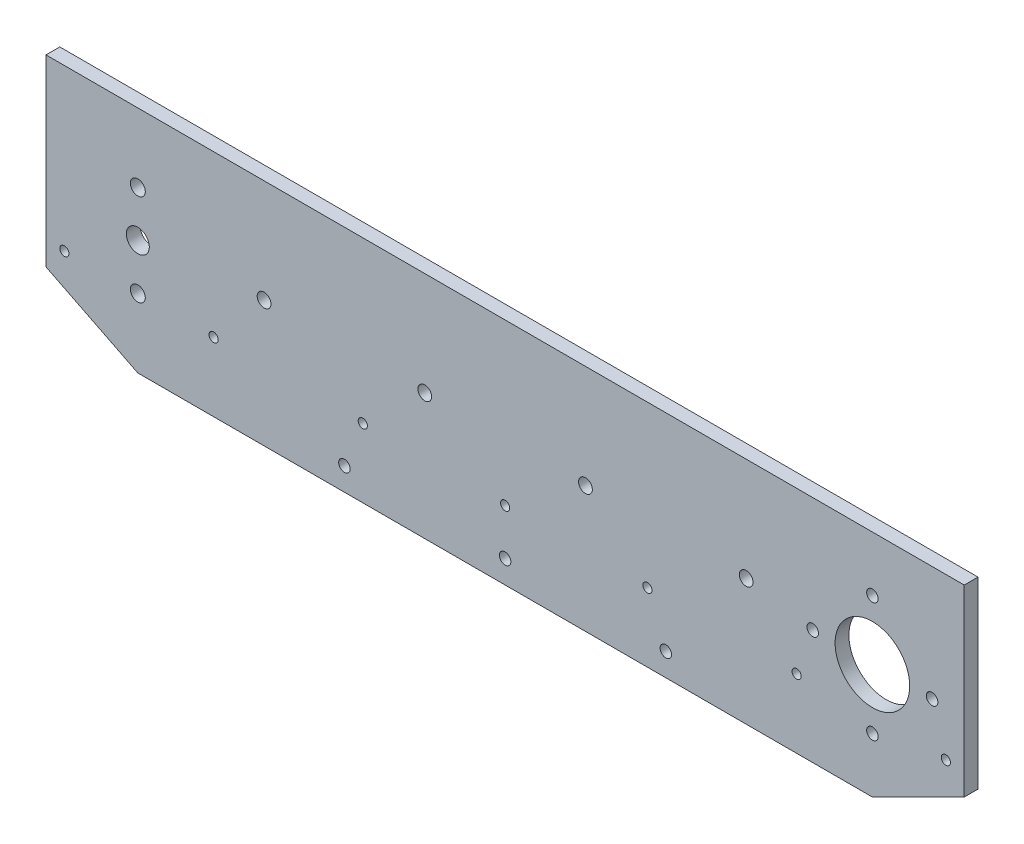
SolidWorks part; units mm, degrees
ref_plane "前基準面" through (0, 0, 0) normal (0, 0, 1) x (1, 0, 0)
ref_plane "上基準面" through (0, 0, 0) normal (0, 1, 0) x (1, 0, 0)
ref_plane "右基準面" through (0, 0, 0) normal (1, 0, 0) x (0, 0, -1)
sketch "草圖1" plane through (0, 0, 0) normal (0, 0, 1) x (1, 0, 0)
  line L1 (-200, 50) -> (200, 50)
  line L2 (-200, 50) -> (-200, -50)
  line L3 (-200, -50) -> (200, -50)
  line L4 (200, 50) -> (200, -50)
  line L5 (-200, 50) -> (200, -50) construction
  line L6 (-200, -50) -> (200, 50) construction
  point P0 (0, 0)
  dimension "D1" = 400
  dimension "D2" = 100
extrude "伸長1" add sketch "草圖1" along normal blind 6
sketch "草圖2" plane through (0, 0, 6) normal (0, 0, 1) x (1, 0, 0)
  line L0 (-200, -30) -> (-160, -50)
  line L1 (-200, 50) -> (-200, -50) construction
  line L2 (-200, -50) -> (200, -50) construction
  line L3 (-160, -50) -> (-200, -50)
  line L4 (-200, -50) -> (-200, -30)
  line L5 (200, -50) -> (200, -30)
  line L6 (200, -50) -> (200, 50) construction
  line L7 (200, -30) -> (160, -50)
  line L8 (160, -50) -> (200, -50)
  line L9 (-200, -30) -> (200, -30) construction
  line L10 (-160, 20) -> (-160, -20) construction
  line L11 (186, 0) -> (134, 0) construction
  line L12 (160, -26) -> (160, -50) construction
  line L13 (160, 26) -> (160, -26) construction
  line L14 (200, 50) -> (-200, 50) construction
  line L15 (-160, -20) -> (-160, -50) construction
  line L16 (-160, 0) -> (160, 0) construction
  circle A0 centre (-160, 0) radius 5
  circle A1 centre (-160, 20) radius 3.25
  circle A2 centre (-160, -20) radius 3.25
  circle A3 centre (160, 0) radius 16.25
  circle A4 centre (160, 26) radius 2.5
  circle A5 centre (134, 0) radius 2.5
  circle A6 centre (186, 0) radius 2.5
  circle A7 centre (160, -26) radius 2.5
  dimension "D4" = 6.5
  dimension "D5" = 10
  dimension "D8" = 5
  dimension "D9" = 32.5
  dimension "D1" = 20
  dimension "D2" = 40
  dimension "D3" = 40
  dimension "D6" = 50
  dimension "D7" = 20
  dimension "D10" = 26
extrude "伸長2" cut sketch "草圖2" against normal through all
sketch "草圖3" plane through (0, 0, 6) normal (0, 0, 1) x (1, 0, 0)
  line L0 (-200, 5) -> (200, 5) construction
  line L1 (-200, 50) -> (-200, -30) construction
  line L2 (200, -30) -> (200, 50) construction
  line L3 (200, -20) -> (-200, -20) construction
  line L4 (-160, -50) -> (160, -50) construction
  line L5 (200, 50) -> (-200, 50) construction
  line L6 (-200, -40) -> (200, -40) construction
  line L7 (0, 0) -> (0, -40) construction
  circle A0 centre (-105, 5) radius 3
  circle A1 centre (-35, 5) radius 3
  circle A2 centre (35, 5) radius 3
  circle A3 centre (105, 5) radius 3
  circle A4 centre (-62, -20) radius 2
  circle A5 centre (0, -20) radius 2
  circle A6 centre (62, -20) radius 2
  circle A7 centre (-192, -20) radius 2
  circle A8 centre (127, -20) radius 2
  circle A9 centre (-127, -20) radius 2
  circle A10 centre (192, -20) radius 2
  circle A11 centre (-70, -40) radius 2.5
  circle A12 centre (0, -40) radius 2.5
  circle A13 centre (70, -40) radius 2.5
  dimension "D1" = 6
  dimension "D2" = 4
  dimension "D12" = 5
  dimension "D3" = 30
  dimension "D4" = 45
  dimension "D5" = 8
  dimension "D6" = 65
  dimension "D7" = 65
  dimension "D8" = 65
  dimension "D9" = 8
  dimension "D10" = 65
  dimension "D11" = 45
  dimension "D13" = 35
  dimension "D14" = 35
  dimension "D15" = 35
  dimension "D16" = 35
  dimension "D17" = 70
  dimension "D18" = 70
extrude "伸長3" cut sketch "草圖3" against normal through all
